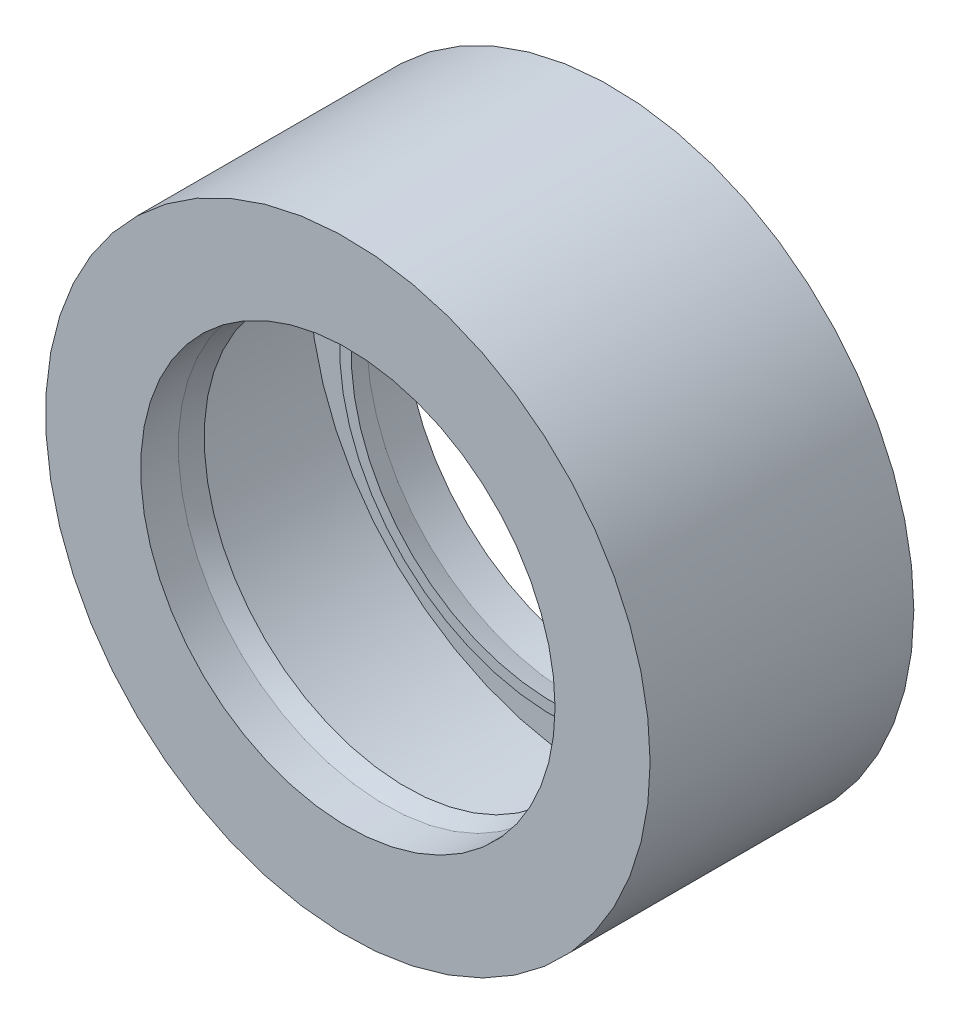
SolidWorks part; units mm, degrees
ref_plane "Front" through (0, 0, 0) normal (0, 0, 1) x (1, 0, 0)
ref_plane "Top" through (0, 0, 0) normal (0, 1, 0) x (1, 0, 0)
ref_plane "Right" through (0, 0, 0) normal (1, 0, 0) x (0, 0, -1)
sketch "草圖1" plane through (0, 0, 0) normal (0, 0, 1) x (1, 0, 0)
  circle A0 centre (0, 0) radius 55
  circle A1 centre (0, 0) radius 80
  dimension "D1" = 110
  dimension "D2" = 160
ref_plane "平面1" through (0, 0, -70) normal (0, 0, 1) x (1, 0, 0)
ref_plane "平面2" through (0, 0, -35) normal (0, 0, 1) x (1, 0, 0)
ref_plane "平面3" through (0, 0, -10) normal (0, 0, 1) x (1, 0, 0)
sketch "草圖3" plane through (0, 0, -70) normal (0, 0, 1) x (1, 0, 0)
  circle A0 centre (0, 0) radius 55
  circle A1 centre (0, 0) radius 80
  dimension "D1" = 160
  dimension "D2" = 110
sketch "草圖4" plane through (0, 0, 0) normal (1, 0, 0) x (0, 0, -1)
  line L0 (0, 55) -> (10, 55)
  line L1 (35, 50) -> (35, -50) construction
  line L2 (70, 55) -> (60, 55)
  line L4 (0, 55) -> (0, 80.2399)
  line L5 (70, 55) -> (70, 80.2399)
  line L6 (0, 80.2399) -> (70, 80.2399)
  line L7 (3, 77.2399) -> (67, 77.2399)
  line L8 (67, 58) -> (67, 77.2399)
  line L9 (67, 58) -> (59.6064, 58)
  line L11 (3, 58) -> (10.3936, 58)
  line L12 (3, 58) -> (3, 77.2399)
  line L13 (35, 80.2399) -> (35, 9.5767) construction
  line L14 (15.5026, 56.7175) -> (15.5026, 53.638)
  line L15 (54.4974, 56.7175) -> (54.4974, 53.638)
  line L17 (33.8192, 53.5218) -> (36.1808, 53.5218) construction
  line L18 (33.6462, 50.5218) -> (36.3538, 50.5218) construction
  arc A1 (10, 55) -> (15.5026, 53.638) centre (52.6336, 215.4486) ccw
  arc A2 (60, 55) -> (54.4974, 53.638) centre (17.3664, 215.4486) cw
  arc A3 (59.6064, 58) -> (54.4974, 56.7175) centre (17.3664, 215.4486) cw
  arc A4 (10.3936, 58) -> (15.5026, 56.7175) centre (52.6336, 215.4486) ccw
  arc A6 (10.3936, 58) -> (33.8192, 53.5218) centre (52.6336, 215.4486) ccw construction
  arc A7 (10, 55) -> (33.6462, 50.5218) centre (52.6336, 215.4486) ccw construction
  arc A8 (60, 55) -> (36.3538, 50.5218) centre (17.3664, 215.4486) cw construction
  arc A9 (59.6064, 58) -> (36.1808, 53.5218) centre (17.3664, 215.4486) cw construction
  dimension "D1" = 10
  dimension "D2" = 3
sketch "草圖6" plane through (0, 0, 0) normal (1, 0, 0) x (0, 0, -1)
  line L0 (0, 0) -> (134.3862, 0) construction
revolve "旋轉1" add sketch "草圖4" angle 360 about L0
